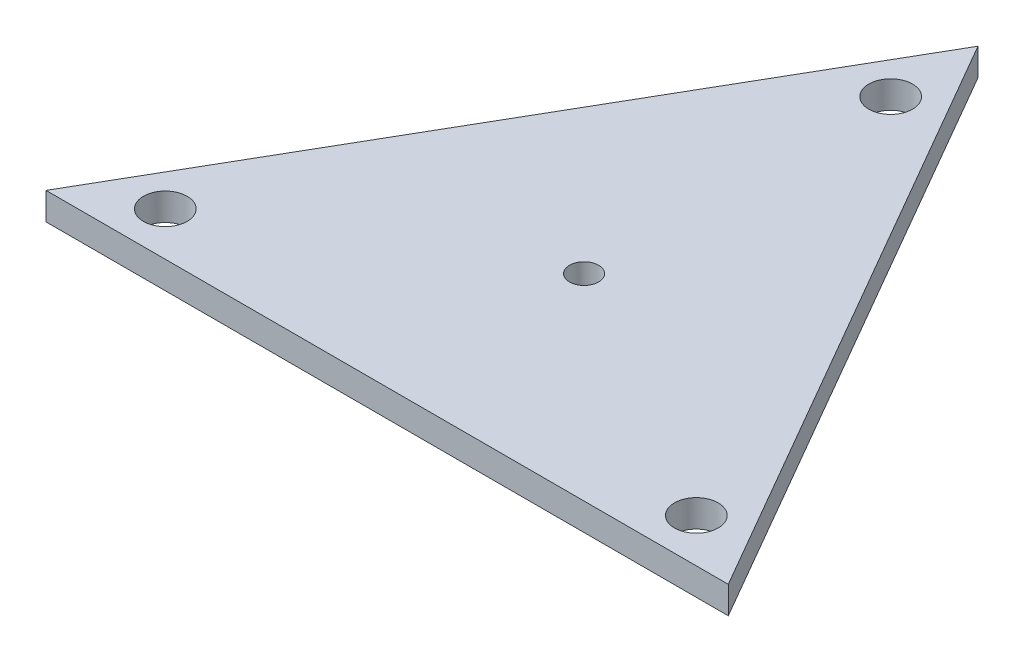
SolidWorks part; units mm, degrees
ref_plane "Front" through (0, 0, 0) normal (0, 0, 1) x (1, 0, 0)
ref_plane "Top" through (0, 0, 0) normal (0, 1, 0) x (1, 0, 0)
ref_plane "Right" through (0, 0, 0) normal (1, 0, 0) x (0, 0, -1)
sketch "Sketch1" plane through (0, 0, 0) normal (0, 1, 0) x (1, 0, 0)
  line L0 (0, 108.2532) -> (62.5, 0)
  line L1 (0, -2.75) -> (0, 2.75) construction
  line L2 (-2.75, 0) -> (2.75, 0) construction
  line L3 (62.5, 0) -> (-62.5, 0)
  line L4 (-62.5, 0) -> (0, 108.2532)
  line L7 (0, 108.2532) -> (0, 0) construction
  point P8 (0, 43.3013)
  dimension "155" = 125
extrude "Boss-Extrude1" add sketch "Sketch1" along normal blind 5
sketch "Sketch2" plane through (0, 5, 0) normal (0, 1, 0) x (1, 0, 0)
  line L0 (0, -2.75) -> (0, 2.75) construction
  line L1 (-2.75, 0) -> (2.75, 0) construction
  line L2 (0, 108.2532) -> (-62.5, 0) construction
  line L3 (62.5, 0) -> (0, 108.2532) construction
  line L4 (0, 108.2532) -> (0, 0) construction
  line L5 (-62.5, 0) -> (31.25, 54.1266) construction
  line L6 (62.5, 0) -> (-31.25, 54.1266) construction
  circle A1 centre (-48.6436, 8) radius 4
  circle A2 centre (48.6436, 8) radius 4
  circle A3 centre (0, 92.2532) radius 4
  circle A4 centre (0, 36.0844) radius 2.6652 construction
  circle A5 centre (0, 36.0844) radius 2.6652
  dimension "D1" = 8
  dimension "D2" = 8
  dimension "D6" = 8
  dimension "D3" = 8
  dimension "D4" = 8
  dimension "D5" = 8
extrude "Cut-Extrude1" cut sketch "Sketch2" against normal through all both and the other way through all
